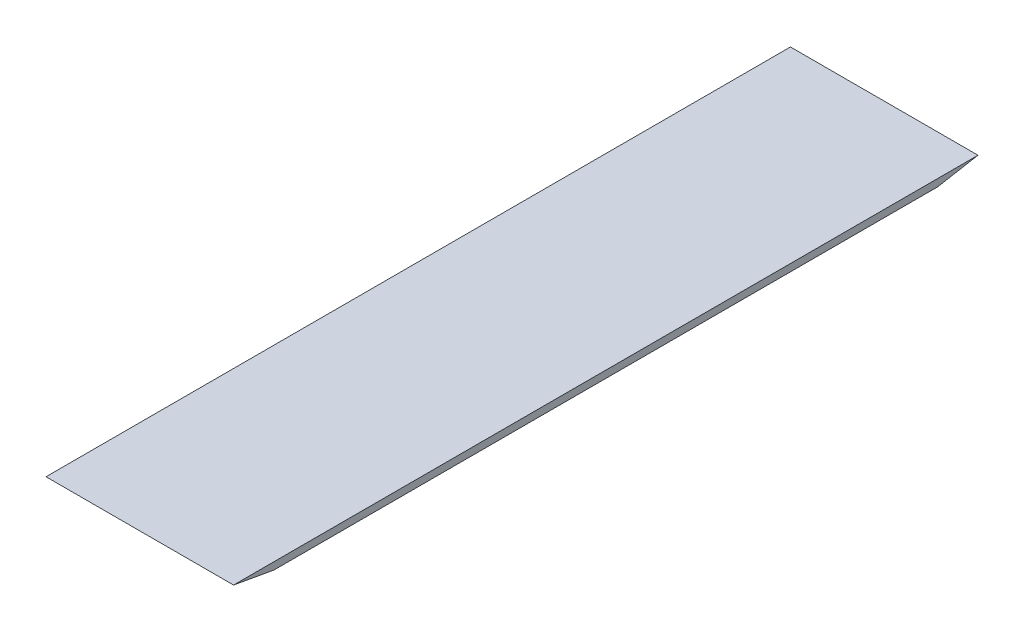
SolidWorks part; units mm, degrees
ref_plane "Front Plane" through (0, 0, 0) normal (0, 0, 1) x (1, 0, 0)
ref_plane "Top Plane" through (0, 0, 0) normal (0, 1, 0) x (1, 0, 0)
ref_plane "Right Plane" through (0, 0, 0) normal (1, 0, 0) x (0, 0, -1)
sketch "Sketch1" plane through (0, 0, 0) normal (1, 0, 0) x (0, 0, -1)
  line L20 (28, -5) -> (488, -5)
  line L21 (488, -5) -> (516, 0)
  line L37 (0, 0) -> (516, 0)
  line L38 (0, 0) -> (28, -5)
  point P0 (0, 0)
  point P6 (1.2193, 5)
  dimension "D1" = 28
  dimension "D2" = 460
  dimension "D3" = 5
  dimension "D8" = 28
extrude "Boss-Extrude1" add sketch "Sketch1" along normal blind 130 contours L20 L21 L37 L38
